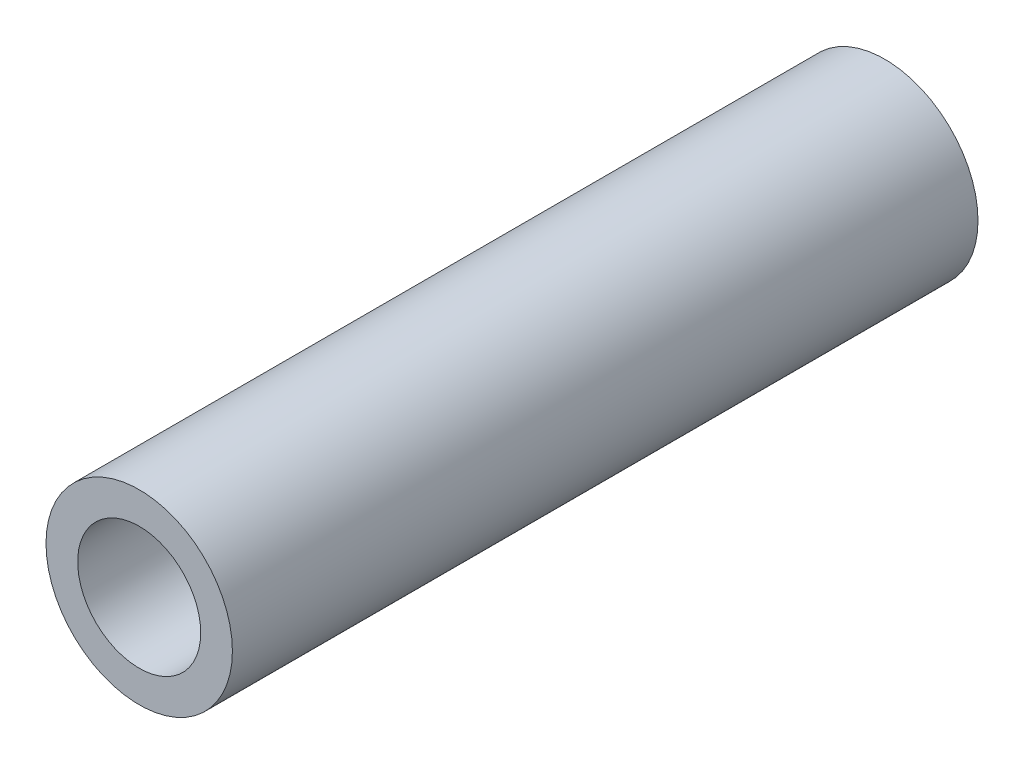
SolidWorks part; units mm, degrees
ref_plane "Front Plane" through (0, 0, 0) normal (0, 0, 1) x (1, 0, 0)
ref_plane "Top Plane" through (0, 0, 0) normal (0, 1, 0) x (1, 0, 0)
ref_plane "Right Plane" through (0, 0, 0) normal (1, 0, 0) x (0, 0, -1)
sketch "Sketch1" plane through (0, 0, 0) normal (0, 0, 1) x (1, 0, 0)
  circle A0 centre (0, 0) radius 2.0955
  circle A1 centre (0, 0) radius 3.175
  dimension "D1" = 6.35
  dimension "D2" = 4.191
extrude "Boss-Extrude1" add sketch "Sketch1" along normal mid plane 25.4
